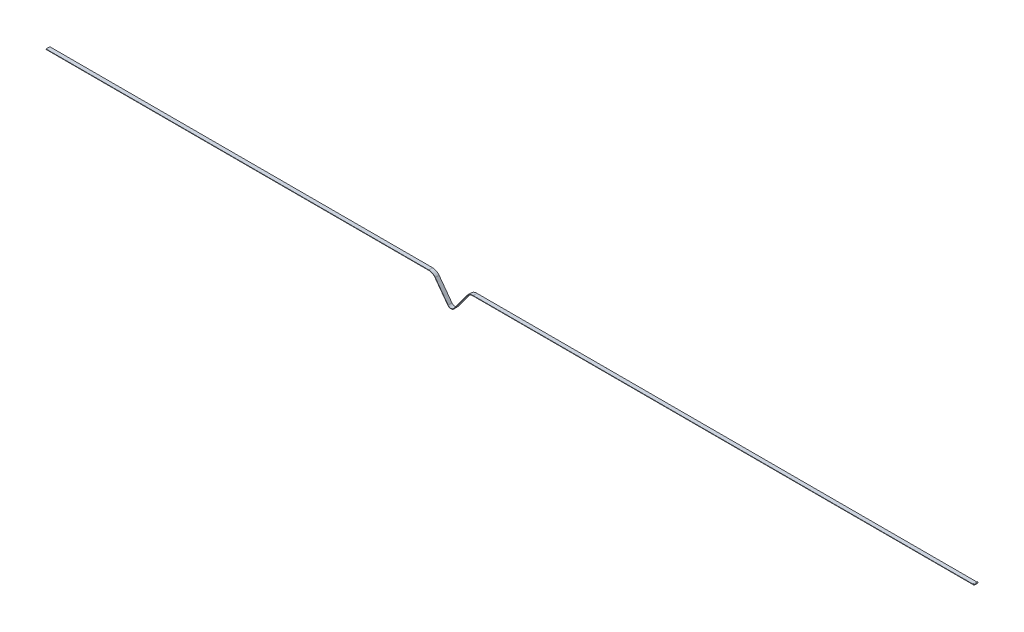
SolidWorks part; units mm, degrees
material "BUTYL"
ref_plane "Front Plane" through (0, 0, 0) normal (0, 0, 1) x (1, 0, 0)
ref_plane "Top Plane" through (0, 0, 0) normal (0, 1, 0) x (1, 0, 0)
ref_plane "Right Plane" through (0, 0, 0) normal (1, 0, 0) x (0, 0, -1)
sketch "Sketch1" plane through (0, 0, 0) normal (1, 0, 0) x (0, 0, -1)
  line L1 (0, 0) -> (6, 0)
  line L2 (0, 0) -> (0, 0.63)
  line L3 (0, 0.63) -> (6, 0.63)
  line L4 (6, 0) -> (6, 0.63)
  dimension "D1" = 0.63
  dimension "D2" = 6
sketch "Sketch2" plane through (0, 0, 0) normal (0, 0, 1) x (1, 0, 0)
  line L0 (0, 0) -> (-781.5813, 0)
  line L1 (-791.214, -4.8779) -> (-811.2262, -32.1359)
  line L2 (-821.0765, -32.1359) -> (-841.0887, -4.8779)
  line L3 (-850.7213, 0) -> (-1447.8, 0)
  arc A0 (-781.5813, 0) -> (-791.214, -4.8779) centre (-781.5813, -11.95) ccw
  arc A1 (-811.2262, -32.1359) -> (-821.0765, -32.1359) centre (-816.1513, -28.52) cw
  arc A2 (-841.0887, -4.8779) -> (-850.7213, 0) centre (-850.7213, -11.95) ccw
  circle A3 centre (-816.1513, -28.52) radius 8 construction
  circle A4 centre (-781.5813, -11.95) radius 11.95 construction
  circle A5 centre (-850.7213, -11.95) radius 11.95 construction
  dimension "D1" = 6.11
  dimension "D4" = 1447.8
sweep "Sweep1" add profiles "Sketch1" path "Sketch2"
sketch "Sketch3" plane through (0, 0, 0) normal (0, 0, 1) x (1, 0, 0)
  line L0 (0, 0.63) -> (-781.5813, 0.63) construction
  line L1 (-1.5, 0.63) -> (-1.5, 0)
  line L2 (0, 0) -> (-781.5813, 0) construction
  line L3 (-1.5, 0) -> (0, 0)
  line L4 (0, 0) -> (0, 0.63)
  arc A1 (0, 0.63) -> (-1.5, 0.63) centre (-0.75, 0.63) ccw
  dimension "D1" = 0.75
extrude "Boss-Extrude1" add sketch "Sketch3" against normal through all
pattern_curve "CrvPattern1" [suppressed] parameters "D1"=2000, "D3"=2, "D2"=1, "D4"=10
